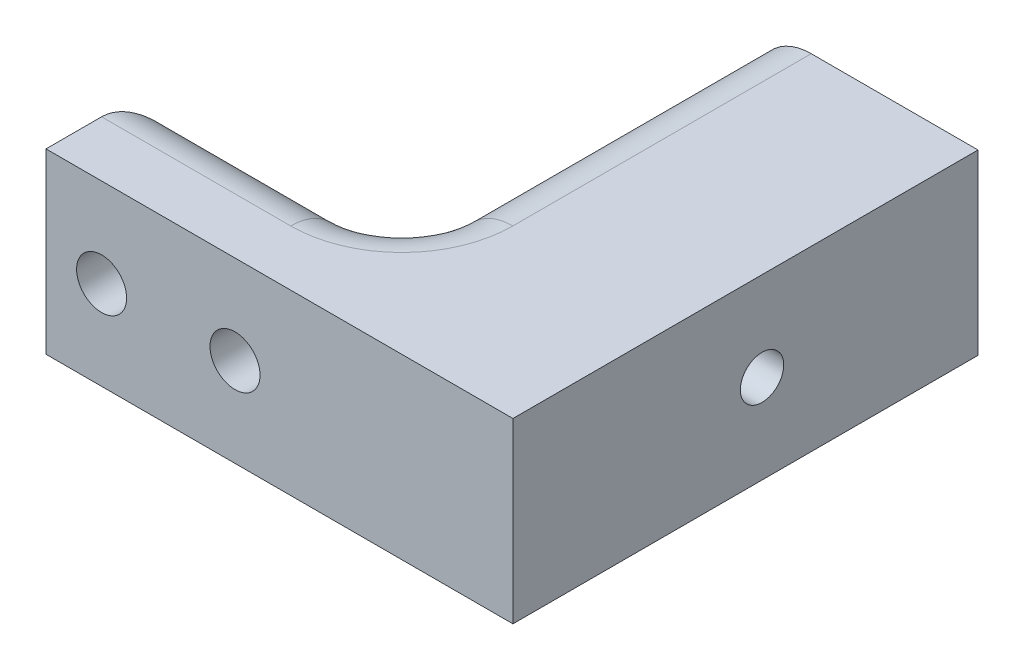
SolidWorks part; units mm, degrees
ref_plane "Plan de face" through (0, 0, 0) normal (0, 0, 1) x (1, 0, 0)
ref_plane "Plan de dessus" through (0, 0, 0) normal (0, 1, 0) x (1, 0, 0)
ref_plane "Plan de droite" through (0, 0, 0) normal (1, 0, 0) x (0, 0, -1)
sketch "Esquisse1" plane through (0, 0, 0) normal (0, 0, 1) x (1, 0, 0)
  line L0 (-21, 8) -> (21, -8) construction
  line L1 (-21, 8) -> (21, 8)
  line L2 (-21, 8) -> (-21, -8)
  line L3 (-21, -8) -> (21, -8)
  line L4 (21, 8) -> (21, -8)
  line L5 (-21, -8) -> (21, 8) construction
  point P4 (0, 0)
  dimension "D1" = 16
  dimension "D2" = 42
extrude "Boss.-Extru.1" add sketch "Esquisse1" along normal blind 41.83
sketch "Esquisse2" plane through (0, -8, 0) normal (0, -1, 0) x (1, 0, 0)
  line L0 (21, 41.83) -> (21, 0) construction
  line L1 (-21, 0) -> (1, 0)
  line L2 (-21, 0) -> (-21, 31.83)
  line L3 (-21, 31.83) -> (1, 31.83)
  line L4 (1, 0) -> (1, 31.83)
  line L5 (-21, 41.83) -> (21, 41.83) construction
  dimension "D1" = 20
  dimension "D2" = 10
extrude "Enlèv. mat.-Extru.1" cut sketch "Esquisse2" against normal through all
fillet "Congé1" radius 5 6 edges at (1, 8, 15.915) (1, -8, 15.915) (1, 0, 31.83) (-10, -8, 31.83) (-10, 8, 31.83) (-21, 0, 31.83)
hole_wizard "Dégagement M3.51" positions "Esquisse3" profile "Esquisse4" hole size "M3.5" standard "Ansi Metric" end condition through all
sketch "Esquisse3" plane through (21, 0, 0) normal (1, 0, 0) x (0, 0, -1)
  line L0 (-41.83, -8) -> (-41.83, 8) construction
  point P0 (-19.425, 0)
  dimension "D1" = 22.405
sketch "Esquisse4" plane through (21, 0, 19.425) normal (0, 1, 0) x (0, 0, -1)
  line L0 (0, 0) -> (0, 42)
  line L1 (0, 42) -> (1.95, 42)
  line L2 (1.95, 42) -> (1.95, 0)
  line L5 (1.95, 0) -> (0, 0)
  line L11 (0, -6.35) -> (0, 107.95) construction
  dimension "Diamètre du perçage jusqu'au prochain" = 3.9
  dimension "Profondeur du perçage jusqu'au prochain" = 42
hole_wizard "Diamètre du perçage Ø4.5 (4.5)2" positions "Esquisse5" profile "Esquisse6" hole size "Ø4.5" standard "Ansi Metric" end condition through all
sketch "Esquisse5" plane through (0, 0, 41.83) normal (0, 0, 1) x (1, 0, 0)
  line L0 (-21, 8) -> (-21, -8) construction
  line L1 (1, 3) -> (1, -3) construction
  point P0 (-16, 0)
  point P2 (-4, 0)
  dimension "D1" = 5
  dimension "D2" = 5
sketch "Esquisse6" plane through (-16, 0, 41.83) normal (1, 0, 0) x (0, -1, 0)
  line L0 (0, 0) -> (0, 41.83)
  line L1 (0, 41.83) -> (2.25, 41.83)
  line L2 (2.25, 41.83) -> (2.25, 0)
  line L5 (2.25, 0) -> (0, 0)
  line L11 (0, -6.35) -> (0, 107.95) construction
  dimension "Diamètre du perçage jusqu'au prochain" = 4.5
  dimension "Profondeur du perçage jusqu'au prochain" = 41.83
sketch "Esquisse7" plane through (1, 0, 0) normal (1, 0, 0) x (0, 0, -1)
  line L1 (-24.1015, 0) -> (-21.7633, -4.05)
  line L2 (-21.7633, -4.05) -> (-17.0867, -4.05)
  line L3 (-17.0867, -4.05) -> (-14.7485, 0)
  line L4 (-14.7485, 0) -> (-17.0867, 4.05)
  line L5 (-17.0867, 4.05) -> (-21.7633, 4.05)
  line L6 (-21.7633, 4.05) -> (-24.1015, 0)
  circle A0 centre (-19.425, 0) radius 4.05 construction
  dimension "D1" = 8.1
extrude "Enlèv. mat.-Extru.2" cut sketch "Esquisse7" along normal blind 17
